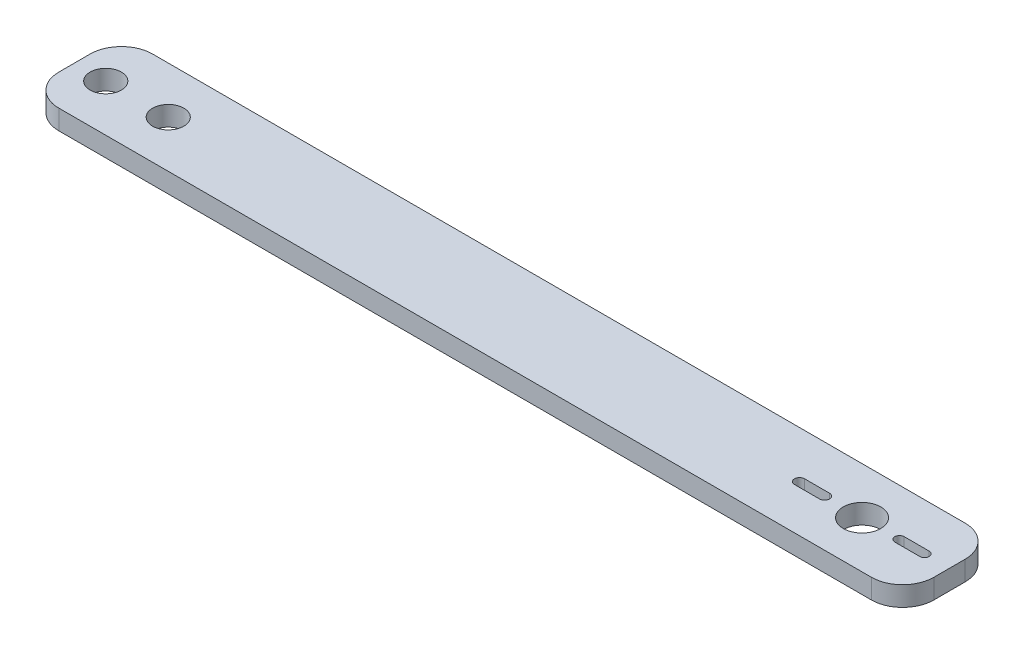
SolidWorks part; units mm, degrees
material "Thornel Mat VMA"
ref_plane "Front Plane" through (0, 0, 0) normal (0, 0, 1) x (1, 0, 0)
ref_plane "Top Plane" through (0, 0, 0) normal (0, 1, 0) x (1, 0, 0)
ref_plane "Right Plane" through (0, 0, 0) normal (1, 0, 0) x (0, 0, -1)
sketch "Sketch1" plane through (0, 0, 0) normal (0, 1, 0) x (1, 0, 0)
  line L1 (-54.398, 16.9499) -> (123.402, 16.9499)
  line L2 (-54.398, 16.9499) -> (-54.398, -2.1001)
  line L3 (-54.398, -2.1001) -> (123.402, -2.1001)
  line L4 (123.402, 16.9499) -> (123.402, -2.1001)
  dimension "D1" = 177.8
  dimension "D2" = 19.05
extrude "Boss-Extrude1" add sketch "Sketch1" along normal blind 4
fillet "Fillet1" radius 6.35 4 edges at (123.402, 2, -16.9499) (123.402, 2, 2.1001) (-54.398, 2, -16.9499) (-54.398, 2, 2.1001)
sketch "Sketch2" plane through (0, 4, 0) normal (0, 1, 0) x (1, 0, 0)
  line L0 (-54.398, 7.4249) -> (-1.9555, 7.4249) construction
  line L1 (-54.398, 10.5999) -> (-54.398, 4.2499) construction
  line L2 (113.242, 7.4249) -> (118.322, 7.4249) construction
  line L3 (113.242, 8.3774) -> (118.322, 8.3774)
  line L4 (113.242, 6.4724) -> (118.322, 6.4724)
  line L5 (98.002, 7.4249) -> (92.922, 7.4249) construction
  line L6 (98.002, 6.4089) -> (92.922, 6.4089)
  line L7 (98.002, 8.4409) -> (92.922, 8.4409)
  line L8 (123.402, 4.2499) -> (123.402, 10.5999) construction
  line L9 (123.402, 7.4249) -> (30.5784, 7.4249) construction
  circle A0 centre (-48.048, 7.4249) radius 3.175
  circle A1 centre (-35.348, 7.4249) radius 3.175
  circle A2 centre (105.622, 7.4249) radius 3.81
  arc A3 (113.242, 8.3774) -> (113.242, 6.4724) centre (113.242, 7.4249) ccw
  arc A4 (118.322, 6.4724) -> (118.322, 8.3774) centre (118.322, 7.4249) ccw
  arc A5 (98.002, 6.4089) -> (98.002, 8.4409) centre (98.002, 7.4249) ccw
  arc A6 (92.922, 8.4409) -> (92.922, 6.4089) centre (92.922, 7.4249) ccw
  point P12 (115.782, 7.4249)
  point P17 (95.462, 7.4249)
  dimension "D1" = 6.35
  dimension "D2" = 6.35
  dimension "D5" = 7.62
  dimension "D10" = 1.905
  dimension "D3" = 6.35
  dimension "D4" = 12.7
  dimension "D6" = 5.08
  dimension "D7" = 5.08
  dimension "D8" = 7.62
  dimension "D9" = 7.62
  dimension "D11" = 2.032
  dimension "D12" = 5.08
extrude "Cut-Extrude1" cut sketch "Sketch2" against normal through all
